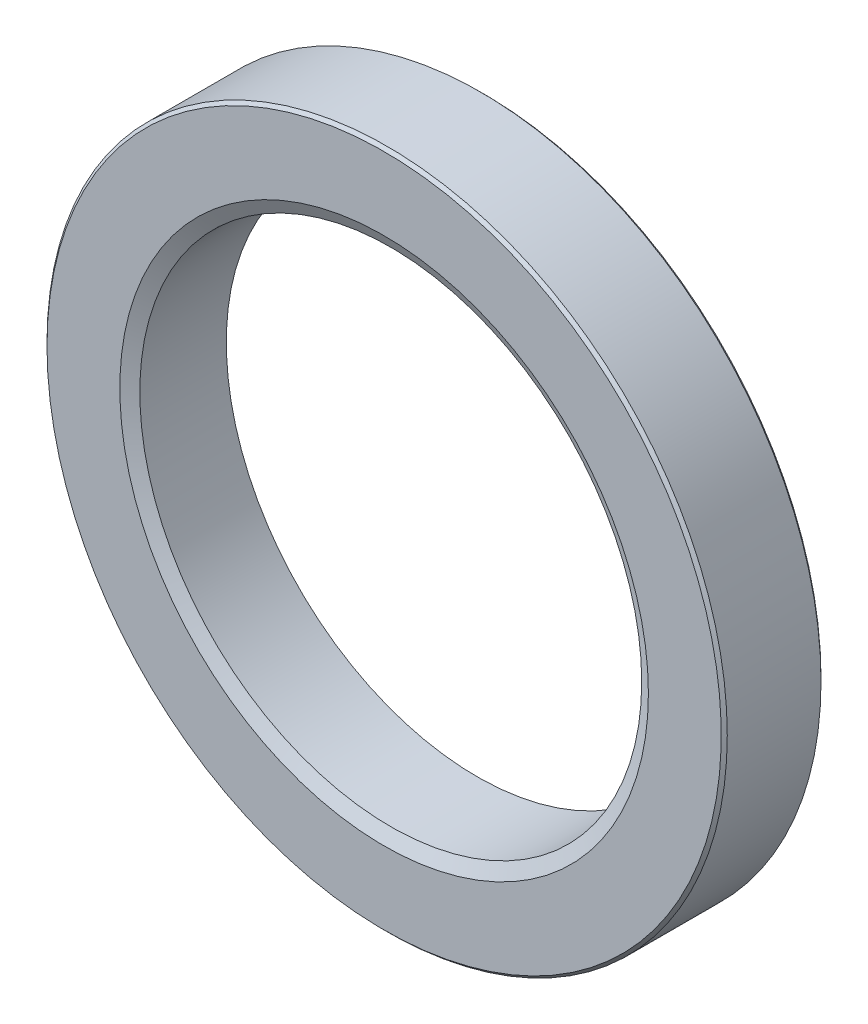
SolidWorks part; units mm, degrees
ref_plane "前视基准面" through (0, 0, 0) normal (0, 0, 1) x (1, 0, 0)
ref_plane "上视基准面" through (0, 0, 0) normal (0, 1, 0) x (1, 0, 0)
ref_plane "右视基准面" through (0, 0, 0) normal (1, 0, 0) x (0, 0, -1)
sketch "草图1" plane through (0, 0, 0) normal (1, 0, 0) x (0, 0, -1)
  line L0 (14.3, 83) -> (-14.3, 83)
  line L1 (0, 55) -> (0, -55) construction
  line L2 (-14.3, 83) -> (-16.5, 87.4125)
  line L3 (-16.5, 87.4125) -> (-16.5, 112.5)
  line L4 (-16.5, 112.5) -> (16.5, 112.5)
  line L5 (0, 112.5) -> (0, 83) construction
  line L6 (-15.0385, 0) -> (11.9293, 0) construction
  line L7 (55, 0) -> (-55, 0) construction
  line L8 (16.5, 87.4125) -> (16.5, 112.5)
  line L9 (14.3, 83) -> (16.5, 87.4125)
  dimension "D1" = 33
  dimension "D2" = 28.6
  dimension "D3" = 166
  dimension "D4" = 225
  dimension "D5" = 26.5
revolve "旋转1" add sketch "草图1" angle 360 about L6
chamfer "倒角1" distance 1 angle 45 2 edges at (112.5, 0, -16.5) (112.5, 0, 16.5)
